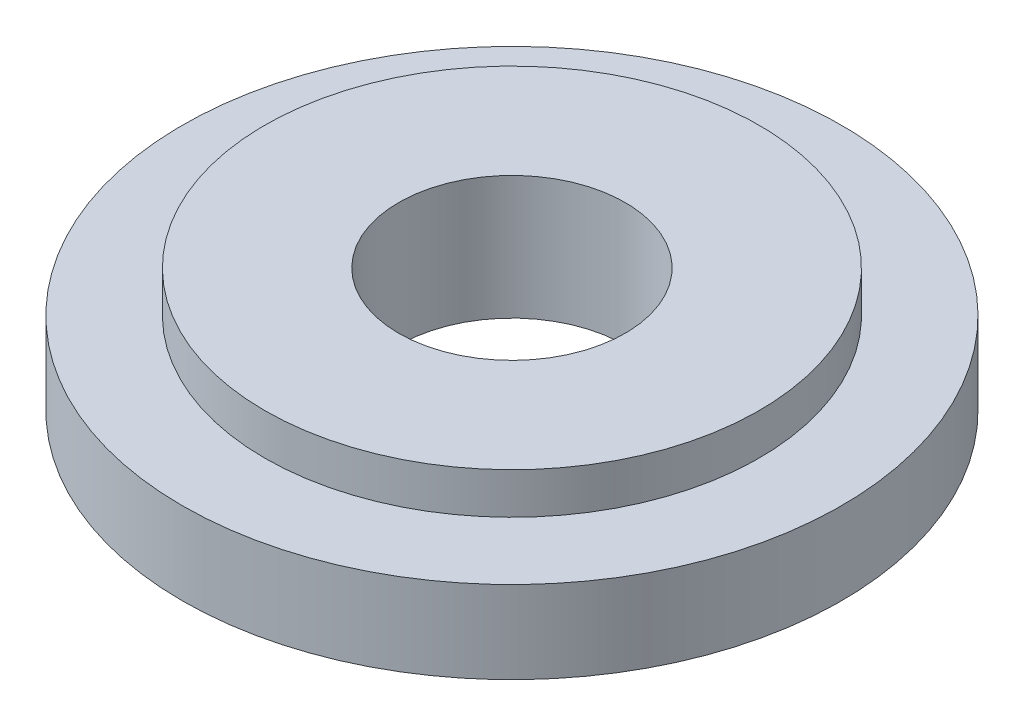
SolidWorks part; units mm, degrees
ref_plane "Front Plane" through (0, 0, 0) normal (0, 0, 1) x (1, 0, 0)
ref_plane "Top Plane" through (0, 0, 0) normal (0, 1, 0) x (1, 0, 0)
ref_plane "Right Plane" through (0, 0, 0) normal (1, 0, 0) x (0, 0, -1)
sketch "Sketch1" plane through (0, 0, 0) normal (0, 1, 0) x (1, 0, 0)
  circle A0 centre (0, 0) radius 2.75
  circle A1 centre (0, 0) radius 8
  dimension "D1" = 16
  dimension "D2" = 5.5
extrude "Boss-Extrude1" add sketch "Sketch1" along normal blind 2
sketch "Sketch3" plane through (0, 2, 0) normal (0, 1, 0) x (1, 0, 0)
  circle A0 centre (0, 0) radius 2.75
  circle A1 centre (0, 0) radius 6
  circle A2 centre (0, 0) radius 2.75 construction
  dimension "D1" = 12
extrude "Boss-Extrude2" add sketch "Sketch3" along normal mid plane 2
